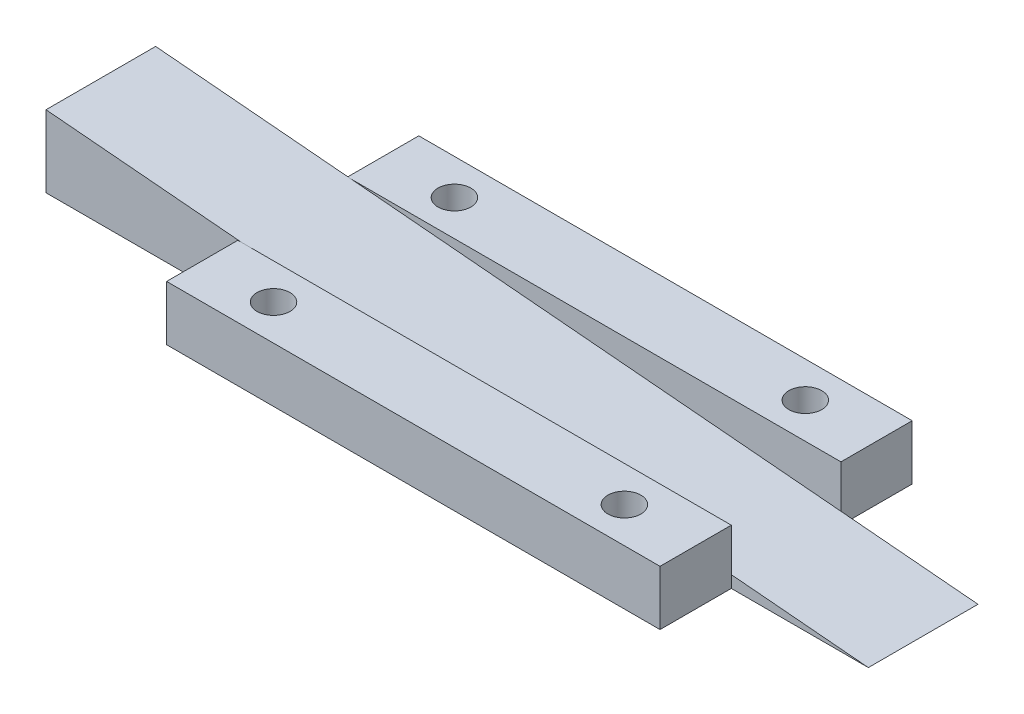
SolidWorks part; units mm, degrees
ref_plane "Front Plane" through (0, 0, 0) normal (0, 0, 1) x (1, 0, 0)
ref_plane "Top Plane" through (0, 0, 0) normal (0, 1, 0) x (1, 0, 0)
ref_plane "Right Plane" through (0, 0, 0) normal (1, 0, 0) x (0, 0, -1)
sketch "Sketch1" plane through (0, 0, 0) normal (0, 0, 1) x (1, 0, 0)
  line L0 (-49.0278, 0) -> (100.9722, 0)
  line L1 (55, 0) -> (-55, 0) construction
  line L2 (100.9722, 0) -> (-49.0278, 13.1233)
  line L3 (-49.0278, 13.1233) -> (-49.0278, 0)
  dimension "D1" = 150
  dimension "D2" = 5
extrude "Boss-Extrude1" add sketch "Sketch1" along normal mid plane 20
sketch "Sketch2" plane through (0, 0, 10) normal (0, 0, 1) x (1, 0, 0)
  line L0 (-14.0278, 0) -> (-14.0278, 10)
  line L1 (-14.0278, 0) -> (75.9722, 0)
  line L2 (-14.0278, 10) -> (75.9722, 10)
  line L3 (75.9722, 0) -> (75.9722, 10)
  line L4 (11, 0) -> (-11, 0) construction
  line L5 (-49.0278, 13.1233) -> (-49.0278, 0) construction
  dimension "D1" = 10
  dimension "D2" = 35
  dimension "D3" = 90
sketch "Sketch3" plane through (0, 0, -10) normal (0, 0, 1) x (1, 0, 0)
  line L0 (-14.0278, 0) -> (-14.0278, 10)
  line L1 (-14.0278, 0) -> (75.9722, 0)
  line L2 (-14.0278, 10) -> (75.9722, 10)
  line L3 (75.9722, 0) -> (75.9722, 10)
  dimension "D1" = 10
  dimension "D3" = 90
extrude "Boss-Extrude2" add sketch "Sketch2" along normal blind 13
extrude "Boss-Extrude3" add sketch "Sketch3" against normal blind 13
sketch "Sketch4" plane through (0, 10, 0) normal (0, -1, 0) x (1, 0, 0)
  line L0 (-1.0278, -16.5) -> (-1.0278, 16.5) construction
  line L1 (-1.0278, 16.5) -> (62.9722, 16.5) construction
  line L2 (62.9722, 16.5) -> (62.9722, -16.5) construction
  line L3 (62.9722, -16.5) -> (-1.0278, -16.5) construction
  line L4 (-14.0278, -23) -> (75.9722, -23) construction
  line L5 (-14.0278, 23) -> (75.9722, 23) construction
  line L6 (75.9722, -23) -> (75.9722, -10) construction
  line L7 (-14.0278, -23) -> (-14.0278, -10) construction
  circle A0 centre (-1.0278, 16.5) radius 3
  circle A1 centre (62.9722, 16.5) radius 3
  circle A2 centre (62.9722, -16.5) radius 3
  circle A3 centre (-1.0278, -16.5) radius 3
  dimension "D1" = 6
  dimension "D2" = 6.5
  dimension "D3" = 6.5
  dimension "D4" = 13
  dimension "D5" = 13
extrude "Cut-Extrude2" cut sketch "Sketch4" along normal blind 13
